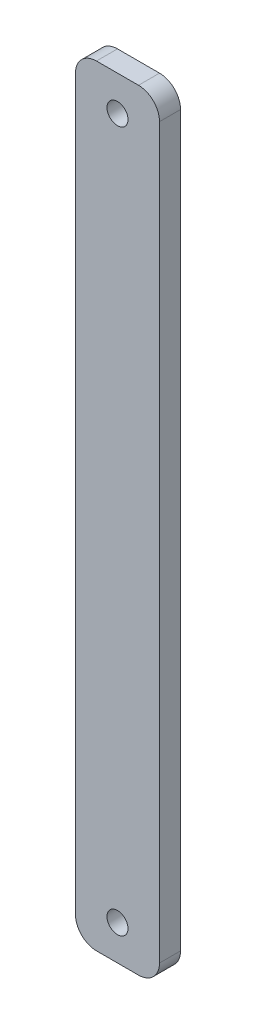
SolidWorks part; units mm, degrees
ref_plane "Alzado" through (0, 0, 0) normal (0, 0, 1) x (1, 0, 0)
ref_plane "Planta" through (0, 0, 0) normal (0, 1, 0) x (1, 0, 0)
ref_plane "Vista lateral" through (0, 0, 0) normal (1, 0, 0) x (0, 0, -1)
sketch "Croquis1" plane through (0, 0, 0) normal (0, 0, 1) x (1, 0, 0)
  line L0 (0, -51.8487) -> (0, 74.7456) construction
  line L1 (-3, -55) -> (3, -55)
  line L2 (-6, -52) -> (-6, 52)
  line L3 (-3, 55) -> (3, 55)
  line L4 (6, -52) -> (6, 52)
  line L5 (-6, -55) -> (6, 55) construction
  line L6 (-6, 55) -> (6, -55) construction
  line L7 (23.9085, 0) -> (-18.7658, 0) construction
  circle A0 centre (0, 50) radius 1.5
  circle A1 centre (0, -50) radius 1.5
  arc A2 (3, -55) -> (6, -52) centre (3, -52) ccw
  arc A3 (-3, -55) -> (-6, -52) centre (-3, -52) cw
  arc A4 (3, 55) -> (6, 52) centre (3, 52) cw
  arc A5 (-6, 52) -> (-3, 55) centre (-3, 52) cw
  point P0 (0, 0)
  dimension "D3" = 3
  dimension "D5" = 3
  dimension "D1" = 12
  dimension "D2" = 110
  dimension "D4" = 5
extrude "Saliente-Extruir1" add sketch "Croquis1" along normal mid plane 3
